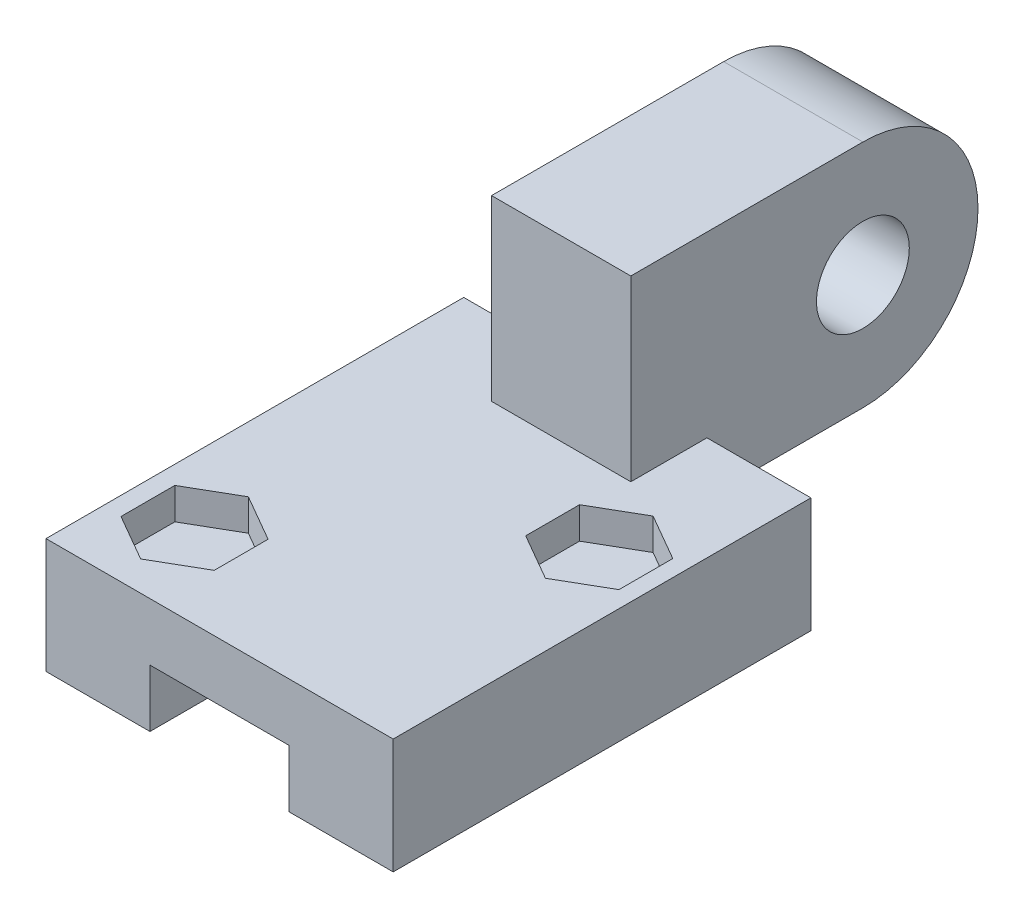
SolidWorks part; units mm, degrees
ref_plane "Alzado" through (0, 0, 0) normal (0, 0, 1) x (1, 0, 0)
ref_plane "Planta" through (0, 0, 0) normal (0, 1, 0) x (1, 0, 0)
ref_plane "Vista lateral" through (0, 0, 0) normal (1, 0, 0) x (0, 0, -1)
sketch "Croquis1" plane through (0, 0, 0) normal (0, 0, 1) x (1, 0, 0)
  line L0 (-1.31, 0) -> (-1.87, 0)
  line L1 (0, 0) -> (-0.56, 0)
  line L2 (0, 0) -> (0, 0.62)
  line L3 (0, 0.62) -> (-1.87, 0.62)
  line L4 (-1.87, 0) -> (-1.87, 0.62)
  line L6 (-0.56, 0) -> (-0.56, 0.31)
  line L7 (-0.56, 0.31) -> (-1.31, 0.31)
  line L8 (-1.31, 0) -> (-1.31, 0.31)
  point P9 (-0.935, 0.62)
  point P10 (-0.935, 0.31)
  dimension "D1" = 0.75
  dimension "D2" = 1.87
  dimension "D3" = 0.31
  dimension "D4" = 0.62
extrude "Saliente-Extruir1" add sketch "Croquis1" along normal blind 2.25
ref_plane "Plano1" through (-0.935, 0, 0) normal (1, 0, 0) x (0, 0, -1)
sketch "Croquis2" plane through (-0.935, 0, 0) normal (1, 0, 0) x (0, 0, -1)
  line L0 (0.84, 1.58) -> (-0.41, 1.58)
  line L1 (-0.41, 1.58) -> (-0.41, 0.62)
  line L2 (-2.25, 0.62) -> (0, 0.62) construction
  line L3 (0.84, 0.34) -> (-0.41, 0.34)
  line L4 (-0.41, 0.34) -> (-0.41, 0.62)
  line L5 (0, 0) -> (0, 0.62) construction
  circle A0 centre (0.84, 0.96) radius 0.25
  arc A1 (0.84, 0.34) -> (0.84, 1.58) centre (0.84, 0.96) ccw
  dimension "D1" = 0.5
  dimension "D2" = 1.24
  dimension "D3" = 0.96
  dimension "D4" = 1.25
  dimension "D5" = 0.41
extrude "Saliente-Extruir2" add sketch "Croquis2" along normal mid plane 0.75
sketch "Croquis3" plane through (0, 0.62, 0) normal (0, 1, 0) x (1, 0, 0)
  line L0 (0, -2.25) -> (-1.87, -2.25) construction
  line L1 (-0.0889, -0.945) -> (-0.0889, -0.655)
  line L2 (-0.0889, -0.655) -> (-0.34, -0.51)
  line L3 (-0.34, -0.51) -> (-0.5911, -0.655)
  line L4 (-0.5911, -0.655) -> (-0.5911, -0.945)
  line L5 (-0.5911, -0.945) -> (-0.34, -1.09)
  line L6 (-0.34, -1.09) -> (-0.0889, -0.945)
  line L7 (-1.2689, -1.945) -> (-1.2689, -1.655)
  line L8 (-1.2689, -1.655) -> (-1.52, -1.51)
  line L9 (-1.52, -1.51) -> (-1.7711, -1.655)
  line L10 (-1.7711, -1.655) -> (-1.7711, -1.945)
  line L11 (-1.7711, -1.945) -> (-1.52, -2.09)
  line L12 (-1.52, -2.09) -> (-1.2689, -1.945)
  line L13 (-1.87, -2.25) -> (-1.87, 0) construction
  circle A0 centre (-0.34, -0.8) radius 0.2511 construction
  circle A1 centre (-1.52, -1.8) radius 0.2511 construction
  dimension "D1" = 1.18
  dimension "D2" = 0.29
  dimension "D3" = 1
  dimension "D4" = 0.45
  dimension "D5" = 0.35
extrude "Cortar-Extruir1" cut sketch "Croquis3" against normal blind 0.17
